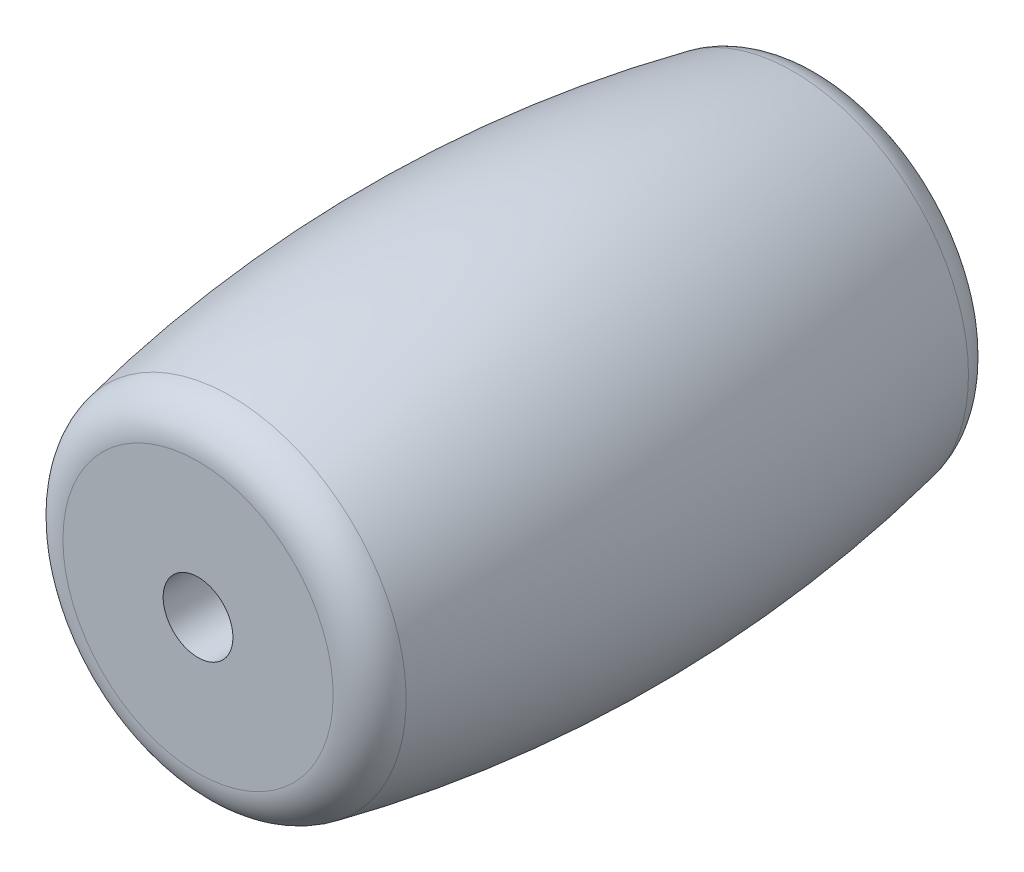
SolidWorks part; units mm, degrees
ref_plane "Ebene vorne" through (0, 0, 0) normal (0, 0, 1) x (1, 0, 0)
ref_plane "Ebene oben" through (0, 0, 0) normal (0, 1, 0) x (1, 0, 0)
ref_plane "Ebene rechts" through (0, 0, 0) normal (1, 0, 0) x (0, 0, -1)
sketch "Skizze1" plane through (0, 0, 0) normal (1, 0, 0) x (0, 0, -1)
  line L0 (-18.8513, 1.3102) -> (22.9868, 1.3102) construction
  line L1 (-15.3, 3.0102) -> (15.3, 3.0102)
  line L2 (-15.3, 3.0102) -> (-15.3, 9.5042)
  line L4 (15.3, 3.0102) -> (15.3, 9.5042)
  line L5 (0, -56.7) -> (0, 24.0864) construction
  arc A1 (15.3, 9.5042) -> (-15.3, 9.5042) centre (0, -56.7) ccw
  point P6 (0, 3.0102)
  dimension "D1" = 30.6
  dimension "D2" = 1.7
revolve "Rotation1" add sketch "Skizze1" angle 360 about L0
fillet "Verrundung1" radius 2 2 edges at (8.1941, 1.3102, -15.3) (8.1941, 1.3102, 15.3)
